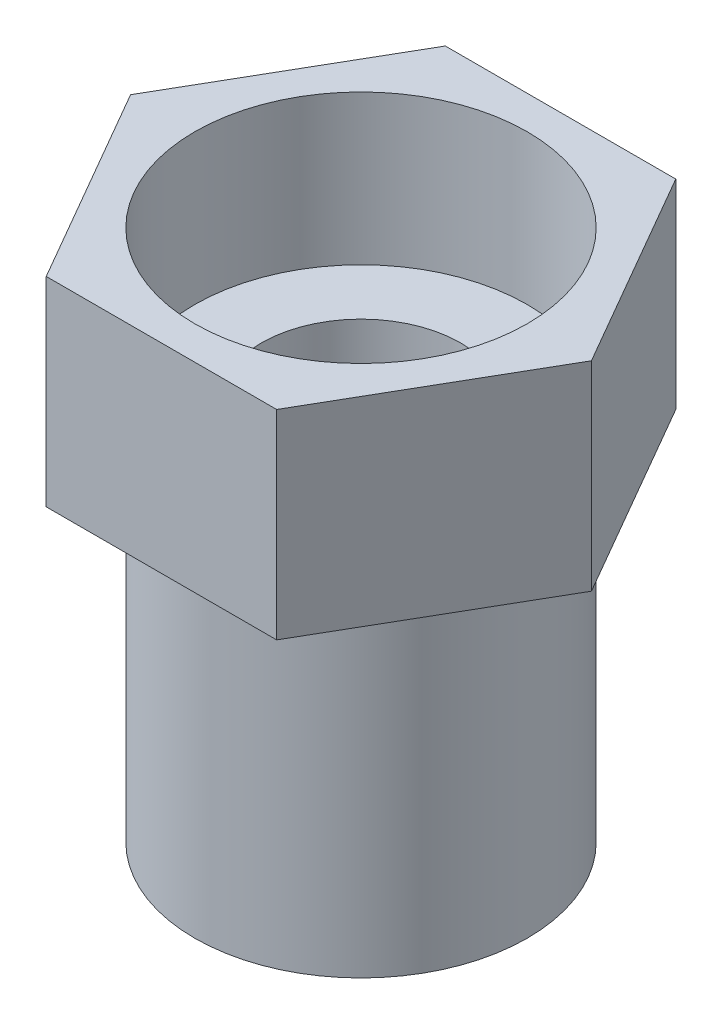
SolidWorks part; units mm, degrees
ref_plane "前视基准面" through (0, 0, 0) normal (0, 0, 1) x (1, 0, 0)
ref_plane "上视基准面" through (0, 0, 0) normal (0, 1, 0) x (1, 0, 0)
ref_plane "右视基准面" through (0, 0, 0) normal (1, 0, 0) x (0, 0, -1)
sketch "草图1" plane through (0, 0, 0) normal (0, 1, 0) x (1, 0, 0)
  line L1 (6.9282, 0) -> (3.4641, 6)
  line L2 (3.4641, 6) -> (-3.4641, 6)
  line L3 (-3.4641, 6) -> (-6.9282, 0)
  line L4 (-6.9282, 0) -> (-3.4641, -6)
  line L5 (-3.4641, -6) -> (3.4641, -6)
  line L6 (3.4641, -6) -> (6.9282, 0)
  circle A0 centre (0, 0) radius 6 construction
  dimension "D1" = 12
extrude "凸台-拉伸1" add sketch "草图1" along normal mid plane 6
sketch "草图2" plane through (0, -3, 0) normal (0, -1, 0) x (1, 0, 0)
  circle A0 centre (0, 0) radius 5
  dimension "D1" = 10
extrude "凸台-拉伸2" add sketch "草图2" along normal blind 10
hole_wizard "M4 六角头螺栓的柱形沉头孔1" positions "草图4" profile "草图5" counterbore size "M4" standard "GB" end condition through all
sketch "草图4" plane through (0, 3, 0) normal (0, 1, 0) x (1, 0, 0)
  point P0 (0, 0)
sketch "草图5" plane through (0, 3, 0) normal (1, 0, 0) x (0, 0, 1)
  line L0 (0, 0) -> (0, 16)
  line L1 (0, 16) -> (3, 16)
  line L3 (3, 16) -> (3, 4.5)
  line L4 (3, 4.5) -> (5, 4.5)
  line L5 (5, 4.5) -> (5, 0)
  line L7 (5, 0) -> (0, 0)
  line L11 (0, -6.35) -> (0, 107.95) construction
  dimension "通孔孔直径" = 6
  dimension "通孔孔深度" = 16
  dimension "柱形沉头孔直径" = 10
  dimension "柱形沉头孔深度" = 4.5
